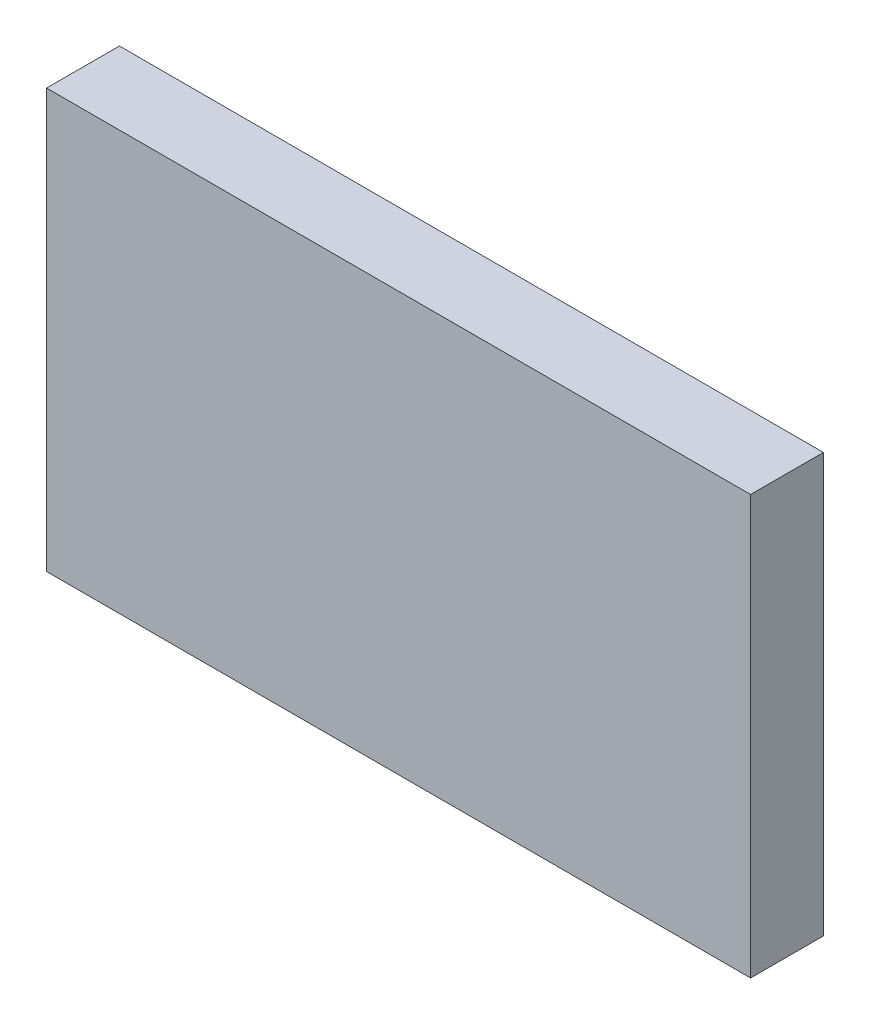
SolidWorks part; units mm, degrees
ref_plane "Front" through (0, 0, 0) normal (0, 0, 1) x (1, 0, 0)
ref_plane "Top" through (0, 0, 0) normal (0, 1, 0) x (1, 0, 0)
ref_plane "Right" through (0, 0, 0) normal (1, 0, 0) x (0, 0, -1)
sketch "Sketch1" plane through (0, 0, 0) normal (0, 0, 1) x (1, 0, 0)
  line L1 (-29, -17.25) -> (29, -17.25)
  line L2 (-29, -17.25) -> (-29, 17.25)
  line L3 (-29, 17.25) -> (29, 17.25)
  line L4 (29, -17.25) -> (29, 17.25)
  line L5 (-29, -17.25) -> (29, 17.25) construction
  line L6 (-29, 17.25) -> (29, -17.25) construction
  point P0 (0, 0)
  dimension "D1" = 58
  dimension "D2" = 34.5
extrude "Boss-Extrude1" add sketch "Sketch1" along normal blind 6
